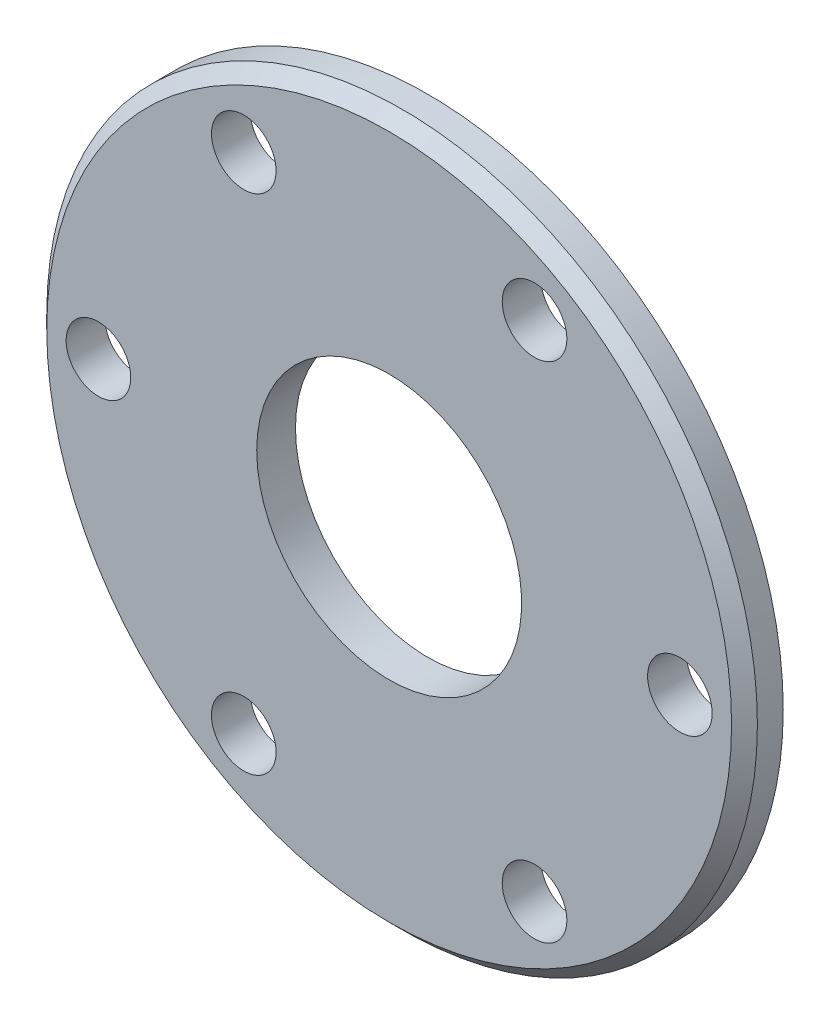
SolidWorks part; units mm, degrees
ref_plane "前视基准面" through (0, 0, 0) normal (0, 0, 1) x (1, 0, 0)
ref_plane "上视基准面" through (0, 0, 0) normal (0, 1, 0) x (1, 0, 0)
ref_plane "右视基准面" through (0, 0, 0) normal (1, 0, 0) x (0, 0, -1)
sketch "草图1" plane through (0, 0, 0) normal (0, 1, 0) x (1, 0, 0)
  line L0 (27.5, 0) -> (0, 0)
  line L1 (0, 0) -> (0, -3)
  line L2 (0, -3) -> (27.5, -3)
  line L3 (27.5, -3) -> (27.5, 0)
  line L4 (0, 0) -> (0, -3) construction
revolve "旋转1" add sketch "草图1" angle 360 about L4
hole_wizard "Ø5.0 (5) 直径孔1" positions "草图3" profile "草图2" hole size "Ø5.0" standard "Ansi Metric"
sketch "草图3" plane through (0, 0, 0) normal (0, 0, -1) x (-1, 0, 0)
  point P0 (-22.5, 0)
  point P1 (-11.25, 19.4856)
  point P2 (11.25, 19.4856)
  point P3 (22.5, 0)
  point P4 (11.25, -19.4856)
  point P5 (-11.25, -19.4856)
sketch "草图2" plane through (22.5, 0, 0) normal (1, 0, 0) x (0, 1, 0)
  line L0 (0, 0) -> (0, 3)
  line L1 (0, 3) -> (2.5, 3)
  line L2 (2.5, 3) -> (2.5, 0)
  line L5 (2.5, 0) -> (0, 0)
  line L11 (0, -6.35) -> (0, 107.95) construction
  dimension "通孔孔直径" = 5
  dimension "通孔孔深度" = 3
hole_wizard "Ø20.5 (20.5) 直径孔1" positions "草图5" profile "草图4" hole size "Ø20.5" standard "Ansi Metric"
sketch "草图5" plane through (0, 0, 0) normal (0, 0, -1) x (-1, 0, 0)
  point P0 (0, 0)
sketch "草图4" plane through (0, 0, 0) normal (1, 0, 0) x (0, 1, 0)
  line L0 (0, 0) -> (0, 3)
  line L1 (0, 3) -> (10.25, 3)
  line L2 (10.25, 3) -> (10.25, 0)
  line L5 (10.25, 0) -> (0, 0)
  line L11 (0, -6.35) -> (0, 107.95) construction
  dimension "通孔孔直径" = 20.5
  dimension "通孔孔深度" = 3
chamfer "倒角1" distance 1 angle 45 1 edges at (27.5, 0, 3)
